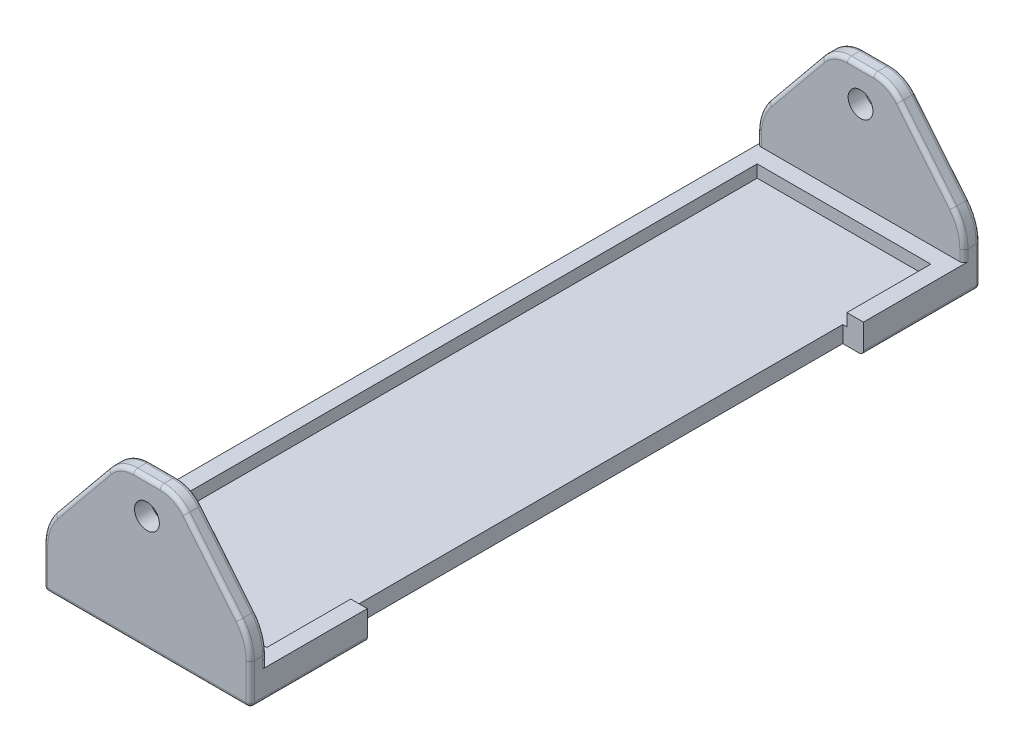
SolidWorks part; units mm, degrees
ref_plane "Front" through (0, 0, 0) normal (0, 0, 1) x (1, 0, 0)
ref_plane "Top" through (0, 0, 0) normal (0, 1, 0) x (1, 0, 0)
ref_plane "Right" through (0, 0, 0) normal (1, 0, 0) x (0, 0, -1)
sketch "草图1" plane through (0, 0, 0) normal (0, 0, 1) x (1, 0, 0)
  line L1 (0, 0) -> (25, 0)
  line L2 (0, 0) -> (0, 3.5)
  line L3 (0, 3.5) -> (25, 3.5)
  line L4 (25, 0) -> (25, 3.5)
  dimension "D1" = 25
  dimension "D2" = 3.5
extrude "凸台-拉伸1" add sketch "草图1" along normal blind 84.3
shell "抽壳1" thickness 2
sketch "草图2" plane through (0, 0, 0) normal (0, -1, 0) x (1, 0, 0)
  line L0 (25, 84.3) -> (25, 0) construction
  line L1 (25, 12.15) -> (22.5, 12.15)
  line L2 (25, 12.15) -> (25, 72.15)
  line L3 (25, 72.15) -> (22.5, 72.15)
  line L4 (22.5, 12.15) -> (22.5, 72.15)
  line L5 (0, 84.3) -> (0, 0) construction
  point P8 (0, 42.15)
  point P9 (25, 42.15)
  dimension "D1" = 60
  dimension "D2" = 2.5
  dimension "D3" = 0
extrude "切除-拉伸1" cut sketch "草图2" against normal through all
sketch "草图3" plane through (0, 0, 0) normal (0, 0, -1) x (-1, 0, 0)
  line L0 (-25, 7) -> (-16, 18)
  line L1 (-25, 0) -> (0, 0)
  line L4 (0, 0) -> (0, 7)
  line L5 (-16, 18) -> (-9, 18)
  line L6 (-9, 18) -> (0, 7)
  line L8 (-25, 7) -> (-25, 0)
  dimension "D1" = 18
  dimension "D2" = 7
  dimension "D3" = 7
  dimension "D4" = 7
  dimension "D5" = 9
extrude "凸台-拉伸2" add sketch "草图3" along normal blind 2
sketch "草图4" plane through (0, 0, 84.3) normal (0, 0, 1) x (1, 0, 0)
  line L0 (0, 0) -> (0, 7)
  line L1 (0, 7) -> (9, 18)
  line L2 (9, 18) -> (16, 18)
  line L3 (16, 18) -> (25, 7)
  line L4 (25, 7) -> (25, 0)
  line L5 (25, 0) -> (0, 0)
extrude "凸台-拉伸3" add sketch "草图4" along normal blind 2
sketch "草图5" plane through (0, 0, 86.3) normal (0, 0, 1) x (1, 0, 0)
  line L0 (16, 18) -> (9, 18) construction
  circle A0 centre (12.5, 14) radius 1.5
  dimension "D1" = 4
extrude "切除-拉伸2" cut sketch "草图5" against normal through all
fillet "圆角1" radius 4 4 edges at (16, 18, -1) (9, 18, -1) (16, 18, 85.3) (9, 18, 85.3)
fillet "圆角2" radius 6 4 edges at (0, 7, 85.3) (25, 7, 85.3) (25, 7, -1) (0, 7, -1)
fillet "圆角3" radius 0.5 36 edges at (25, 4.1791, 84.3) (24.6508, 6.8753, 84.3) (20.422, 12.5953, 84.3) (15.8174, 17.6147, 84.3) (0, 4.1791, 84.3) (0.3492, 6.8753, 84.3) (4.578, 12.5953, 84.3) (9.1826, 17.6147, 84.3) (25, 2.4291, 86.3) (24.6508, 6.8753, 86.3) (20.422, 12.5953, 86.3) (15.8174, 17.6147, 86.3) (0, 2.4291, 86.3) (0.3492, 6.8753, 86.3) (4.578, 12.5953, 86.3) (9.1826, 17.6147, 86.3) (0, 2.4291, -2) (0.3492, 6.8753, -2) (4.578, 12.5953, -2) (9.1826, 17.6147, -2) (25, 2.4291, -2) (24.6508, 6.8753, -2) (20.422, 12.5953, -2) (15.8174, 17.6147, -2) (0, 4.1791, 0) (0.3492, 6.8753, 0) (4.578, 12.5953, 0) (9.1826, 17.6147, 0) (25, 4.1791, 0) (24.6508, 6.8753, 0) (20.422, 12.5953, 0) (15.8174, 17.6147, 0) (12.5, 18, 84.3) (12.5, 18, 86.3) (12.5, 18, -2) (12.5, 18, 0)
fillet "圆角4" radius 0.5 8 edges at (25, 0, 78.975) (24.8536, 0, -1.8536) (12.5, 0, -2) (0.1464, 0, -1.8536) (0, 0, 42.15) (0.1464, 0, 86.1536) (24.8536, 0, 86.1536) (12.5, 0, 86.3)
